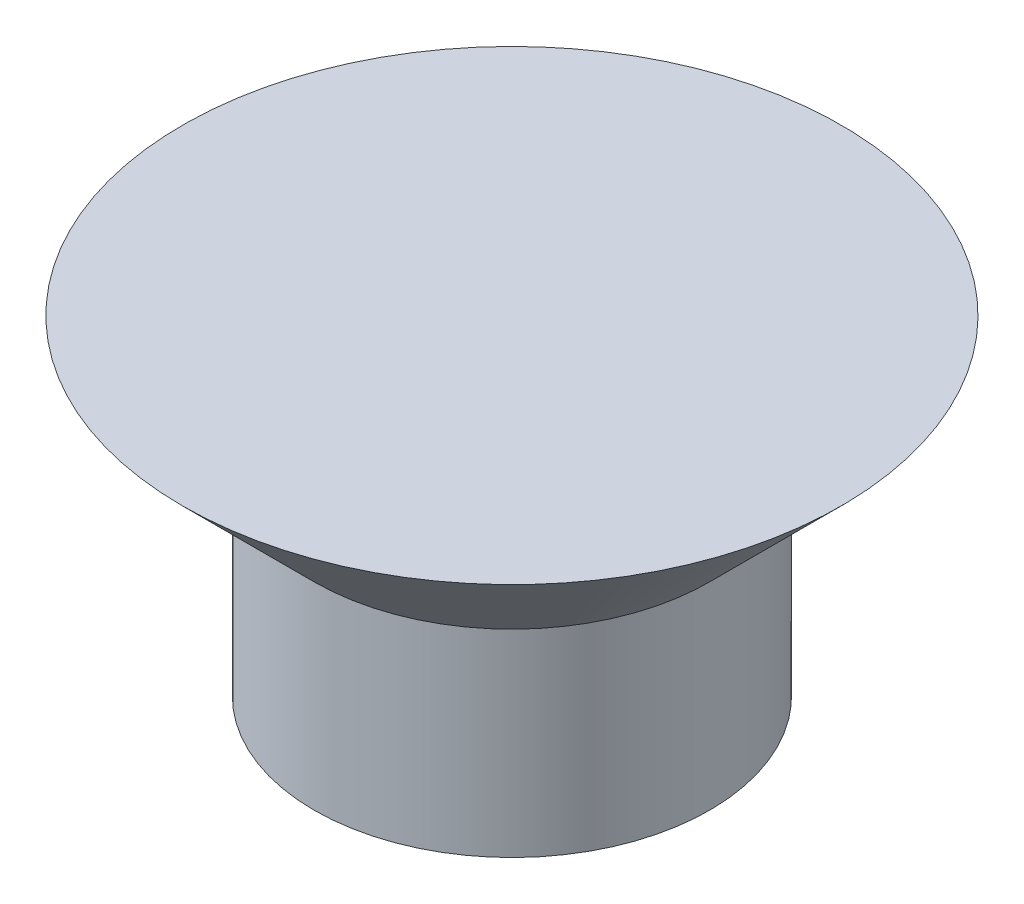
SolidWorks part; units mm, degrees
ref_plane "Front Plane" through (0, 0, 0) normal (0, 0, 1) x (1, 0, 0)
ref_plane "Top Plane" through (0, 0, 0) normal (0, 1, 0) x (1, 0, 0)
ref_plane "Right Plane" through (0, 0, 0) normal (1, 0, 0) x (0, 0, -1)
sketch "Sketch1" plane through (0, 0, 0) normal (0, 0, 1) x (1, 0, 0)
  line L0 (-24.5038, -36.4962) -> (-22.0038, -36.4962)
  line L1 (-24.5038, -36.4962) -> (-24.5038, -38.9962)
  line L2 (-24.5038, -38.9962) -> (-23.0038, -38.9962)
  line L3 (-23.0038, -38.9962) -> (-23.0038, -37.4962)
  line L4 (-23.0038, -37.4962) -> (-22.0038, -36.4962)
  dimension "D1" = 2.5
  dimension "D2" = 2.5
  dimension "D3" = 1.5
  dimension "1.5" = 1.5
revolve "Revolve1" add sketch "Sketch1" angle 360 about L1
sketch "Orientation Sketch" plane through (0, -36.4962, 0) normal (0, 1, 0) x (1, 0, 0)
  circle A0 centre (-24.5038, 0) radius 2.5 construction
  circle A1 centre (-24.5038, 0) radius 2.5
  point P3 (-24.5038, 0)
other "FormTool1"
